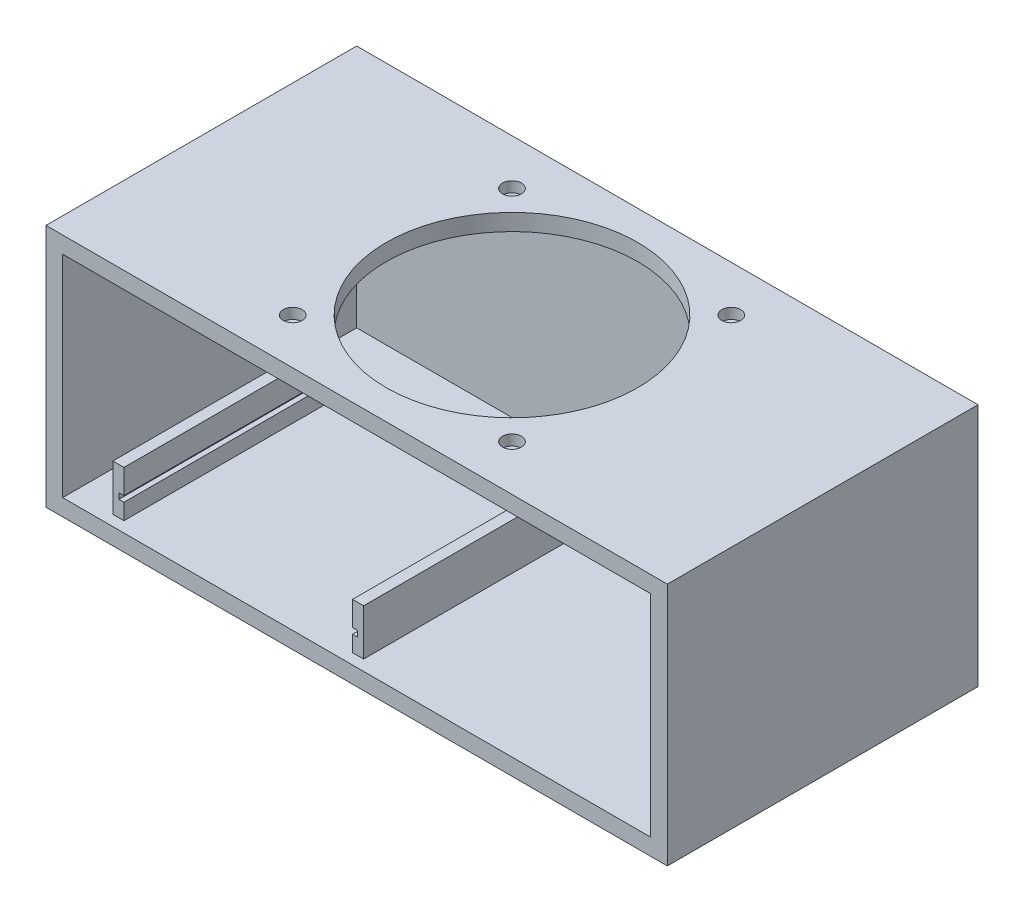
SolidWorks part; units mm, degrees
ref_plane "Front Plane" through (0, 0, 0) normal (0, 0, 1) x (1, 0, 0)
ref_plane "Top Plane" through (0, 0, 0) normal (0, 1, 0) x (1, 0, 0)
ref_plane "Right Plane" through (0, 0, 0) normal (1, 0, 0) x (0, 0, -1)
sketch "Sketch1" plane through (0, 0, 0) normal (0, 1, 0) x (1, 0, 0)
  line L1 (-88.9, -44.45) -> (88.9, -44.45)
  line L2 (-88.9, -44.45) -> (-88.9, 44.45)
  line L3 (-88.9, 44.45) -> (88.9, 44.45)
  line L4 (88.9, -44.45) -> (88.9, 44.45)
  line L5 (-88.9, -44.45) -> (88.9, 44.45) construction
  line L6 (-88.9, 44.45) -> (88.9, -44.45) construction
  point P0 (0, 0)
extrude "Boss-Extrude1" add sketch "Sketch1" along normal blind 69.85
sketch "Sketch3" plane through (0, 69.85, 0) normal (0, 1, 0) x (1, 0, 0)
  circle A0 centre (0, 0) radius 36
shell "Shell1" thickness 4.7625
extrude "Cut-Extrude1" cut sketch "Sketch3" against normal blind 57.912
sketch "Sketch4" plane through (0, 69.85, 0) normal (0, 1, 0) x (1, 0, 0)
  line L0 (0, 0) -> (0, 36) construction
  line L1 (0, 0) -> (0, -36) construction
  line L2 (0, 0) -> (36, 0) construction
  line L3 (0, 0) -> (-31.3736, -31.3736) construction
  line L4 (0, 0) -> (31.3736, 31.3736) construction
  line L5 (0, 0) -> (31.3736, -31.3736) construction
  line L6 (0, 0) -> (-31.3736, 31.3736) construction
  circle A0 centre (0, 0) radius 36 construction
  circle A1 centre (-31.3736, 31.3736) radius 2.7
  circle A2 centre (31.3736, 31.3736) radius 2.7
  circle A3 centre (31.3736, -31.3736) radius 2.7
  circle A4 centre (-31.3736, -31.3736) radius 2.7
extrude "Cut-Extrude4" cut sketch "Sketch4" against normal blind 3 contours A4 | A3 | A2 | A1
sketch "Sketch5" plane through (0, 4.7625, 0) normal (0, 1, 0) x (1, 0, 0)
  line L0 (-84.1375, -44.45) -> (-66.4718, -44.45)
  line L1 (-84.1375, -44.45) -> (84.1375, -44.45) construction
  line L7 (-69.6468, -41.4011) -> (-69.6468, 17.5497) construction
  line L8 (-69.6468, 17.5497) -> (-1.0668, 17.5497) construction
  line L9 (-1.0668, 17.5497) -> (-1.0668, -41.4011) construction
  line L10 (-1.0668, -41.4011) -> (-69.6468, -41.4011) construction
  line L12 (-35.3568, 17.5497) -> (-35.3568, -41.4011) construction
  line L13 (-1.0668, 0) -> (-4.2418, 0) construction
  line L14 (-4.2418, 17.5497) -> (-4.2418, -41.4011)
  line L15 (-4.2418, -41.4011) -> (-1.0668, -41.4011)
  line L16 (-1.0668, -41.4011) -> (-1.0668, 17.5497)
  line L17 (-1.0668, 17.5497) -> (-4.2418, 17.5497)
  line L19 (-69.6468, -41.4011) -> (-69.6468, 17.5497)
  line L22 (-72.8218, 17.5497) -> (-72.8218, 0)
  line L27 (-69.6468, -38.5957) -> (-1.0668, 14.7443) construction
  line L28 (-69.6468, 14.7443) -> (-1.0668, -38.5957) construction
  line L29 (-72.8218, 0) -> (-72.8218, -41.4011)
  line L30 (-72.8218, 17.5497) -> (-69.6468, 17.5497)
  line L31 (-72.8218, -41.4011) -> (-69.6468, -41.4011)
  point P6 (-35.3568, -11.9257)
  point P16 (-35.3568, 17.5497)
extrude "Boss-Extrude4" add sketch "Sketch5" along normal blind 13.208 contours L16 L17 L14 L15 | L19 L30 L22 L29 L31
sketch "Sketch8" plane through (0, 0, 41.4011) normal (0, 0, 1) x (1, 0, 0)
  line L0 (-69.6468, 4.7625) -> (-69.6468, 9.3345) construction
  line L1 (-69.6468, 17.9705) -> (-69.6468, 4.7625) construction
  line L2 (-69.6468, 9.3345) -> (-69.6468, 10.9855) construction
  line L3 (-69.6468, 10.9855) -> (-71.0939, 10.9855)
  line L4 (-71.0939, 10.9855) -> (-71.0939, 9.3345)
  line L5 (-71.0939, 9.3345) -> (-69.6468, 9.3345)
  line L6 (-69.6468, 9.3345) -> (-69.6468, 10.9855)
  line L7 (-69.6468, 17.9705) -> (-4.2418, 17.9705) construction
  line L8 (-36.9443, 17.9705) -> (-36.9443, -3.6929) construction
  line L9 (-2.7947, 9.3345) -> (-4.2418, 9.3345)
  line L10 (-2.7947, 10.9855) -> (-2.7947, 9.3345)
  line L11 (-4.2418, 10.9855) -> (-2.7947, 10.9855)
  line L12 (-4.2418, 9.3345) -> (-4.2418, 10.9855)
extrude "Cut-Extrude8" cut sketch "Sketch8" against normal blind 56.134
